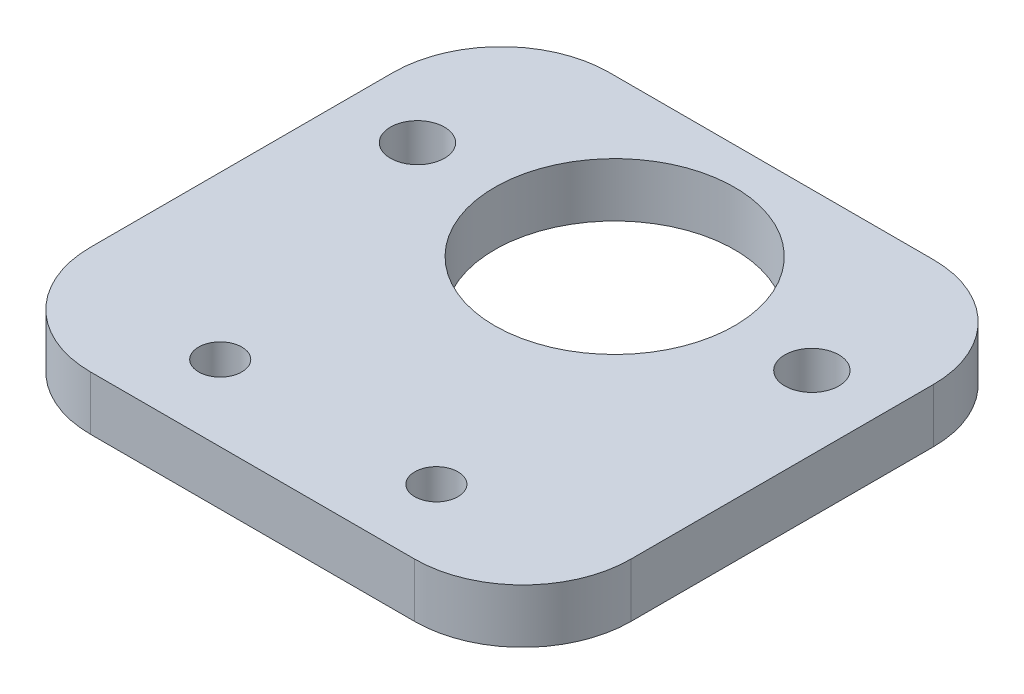
SolidWorks part; units mm, degrees
ref_plane "Plano frontal" through (0, 0, 0) normal (0, 0, 1) x (1, 0, 0)
ref_plane "Plano superior" through (0, 0, 0) normal (0, 1, 0) x (1, 0, 0)
ref_plane "Plano direito" through (0, 0, 0) normal (1, 0, 0) x (0, 0, -1)
sketch "Esboço1" plane through (0, 0, 0) normal (0, 1, 0) x (1, 0, 0)
  line L1 (0, 0) -> (50, 0)
  line L2 (0, 0) -> (0, 48)
  line L3 (0, 48) -> (50, 48)
  line L4 (50, 0) -> (50, 48)
  dimension "D1" = 50
  dimension "D2" = 48
extrude "Ressalto-extrusão1" add sketch "Esboço1" along normal blind 5
sketch "Esboço2" plane through (0, 5, 0) normal (0, 1, 0) x (1, 0, 0)
  line L0 (25, -4.1715) -> (25, 52.0511) construction
  line L1 (50, 48) -> (0, 48) construction
  line L2 (-4.2144, 33.5) -> (62.308, 33.5) construction
  circle A0 centre (25, 33.5) radius 11.1
  circle A1 centre (6.75, 33.5) radius 2.5
  circle A2 centre (43.25, 33.5) radius 2.5
  dimension "D2" = 22.2
  dimension "D3" = 14.5
  dimension "D4" = 18.25
  dimension "D5" = 5
  dimension "D1" = 25
extrude "Corte-extrusão1" cut sketch "Esboço2" against normal blind 5
fillet "Filete1" radius 10 1 edges at (50, 2.5, 0)
fillet "Filete2" radius 10 1 edges at (0, 2.5, 0)
fillet "Filete3" radius 10 1 edges at (50, 2.5, -48)
fillet "Filete4" radius 10 1 edges at (0, 2.5, -48)
sketch "Esboço3" plane through (0, 5, 0) normal (0, 1, 0) x (1, 0, 0)
  line L0 (25, -3.389) -> (25, 53.125) construction
  line L1 (-6.2053, 7) -> (60.7128, 7) construction
  circle A0 centre (15, 7) radius 2
  circle A1 centre (35, 7) radius 2
  dimension "D3" = 10
  dimension "D4" = 4
  dimension "D1" = 7
  dimension "D2" = 25
extrude "Corte-extrusão2" cut sketch "Esboço3" against normal blind 22
